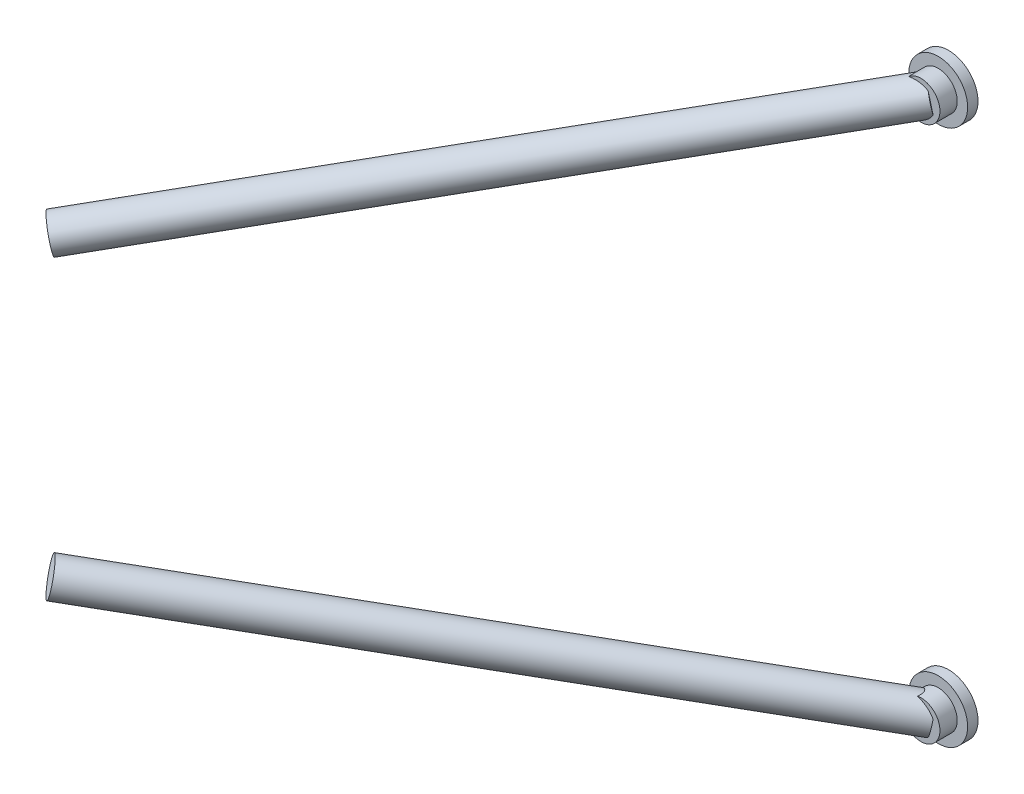
SolidWorks part; units mm, degrees
material "AISI Type 316L stainless steel"
ref_plane "Front Plane" through (0, 0, 0) normal (0, 0, 1) x (1, 0, 0)
ref_plane "Top Plane" through (0, 0, 0) normal (0, 1, 0) x (1, 0, 0)
ref_plane "Right Plane" through (0, 0, 0) normal (1, 0, 0) x (0, 0, -1)
sketch "Pipe sketch 1" plane through (0, 0, 0) normal (0, 0, 1) x (1, 0, 0)
  circle A0 centre (0, 0) radius 10
  dimension "D1" = 20
extrude "Pipe 1" add sketch "Pipe sketch 1" along normal blind 366.4724 separate body
move or copy body "Pipe rotate 1" bodies to move or copy 101 copy no rotation origin (0, 0, 0) rotation axis (-1, 0, 0) rotation angle 164.859
move or copy body "Pipe rotate 2" bodies to move or copy 102 copy no rotation origin (0, 0, 0) rotation axis (0, 1, 0) rotation angle 43.876
move or copy body "Pipe rotate 3" bodies to move or copy 103 copy no rotation origin (0, 0, 0) rotation axis (0, 0, -1) rotation angle 143.476
move or copy body "Pipe place 1" bodies to move or copy 104 copy no translate (126, 86, 568) parameters "D1"=126, "D2"=86, "D3"=568
sketch "Extrude sketch 1" plane through (0, 0, 0) normal (0, 0, 1) x (1, 0, 0)
  circle A0 centre (380, 155) radius 17
  dimension "D1" = 34
extrude "Extrude 1" add sketch "Extrude sketch 1" along normal blind 6 from offset 303 separate body
sketch "Extrude sketch 2" plane through (0, 0, 0) normal (0, 0, 1) x (1, 0, 0)
  circle A0 centre (380, 155) radius 11
  dimension "D1" = 22
extrude "Extrude 2" add sketch "Extrude sketch 2" along normal blind 10 from offset 309 separate body
sketch "Pipe sketch 2" plane through (0, 0, 0) normal (0, 0, 1) x (1, 0, 0)
  circle A0 centre (0, 0) radius 10
  dimension "D1" = 20
extrude "Pipe 2" add sketch "Pipe sketch 2" along normal blind 366.4724 separate body
move or copy body "Pipe rotate 4" bodies to move or copy 108 copy no rotation origin (0, 0, 0) rotation axis (1, 0, 0) rotation angle 164.859
move or copy body "Pipe rotate 5" bodies to move or copy 109 copy no rotation origin (0, 0, 0) rotation axis (0, 1, 0) rotation angle 43.876
move or copy body "Pipe rotate 6" bodies to move or copy 110 copy no rotation origin (0, 0, 0) rotation axis (0, 0, 1) rotation angle 143.476
move or copy body "Pipe place 2" bodies to move or copy 111 copy no translate (126, -86, 568) parameters "D1"=126, "D2"=86, "D3"=568
sketch "Extrude sketch 3" plane through (0, 0, 0) normal (0, 0, 1) x (1, 0, 0)
  circle A0 centre (380, -155) radius 17
  dimension "D1" = 34
extrude "Extrude 3" add sketch "Extrude sketch 3" along normal blind 6 from offset 303 separate body
sketch "Extrude sketch 4" plane through (0, 0, 0) normal (0, 0, 1) x (1, 0, 0)
  circle A0 centre (380, -155) radius 11
  dimension "D1" = 22
extrude "Extrude 4" add sketch "Extrude sketch 4" along normal blind 10 from offset 309 separate body
